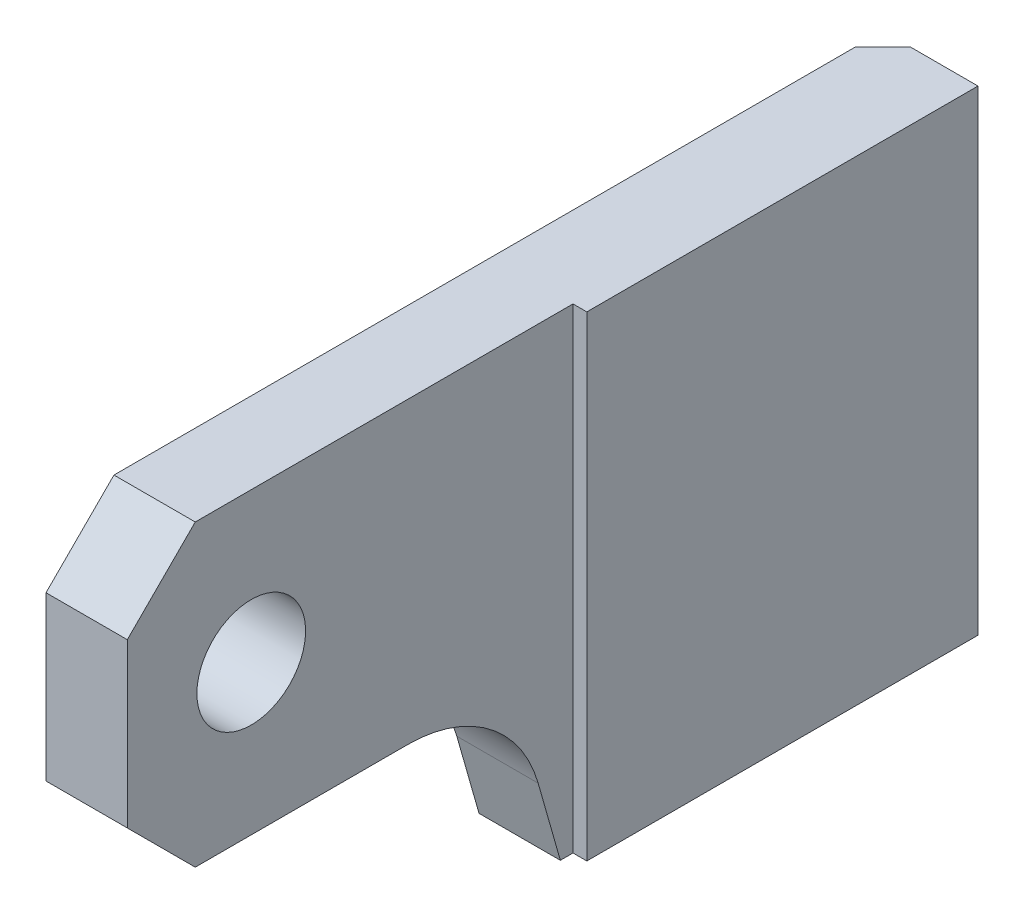
SolidWorks part; units mm, degrees
ref_plane "Спереди" through (0, 0, 0) normal (0, 0, 1) x (1, 0, 0)
ref_plane "Сверху" through (0, 0, 0) normal (0, 1, 0) x (1, 0, 0)
ref_plane "Справа" through (0, 0, 0) normal (1, 0, 0) x (0, 0, -1)
sketch "Эскиз1" plane through (0, 0, 0) normal (1, 0, 0) x (0, 0, -1)
  line L0 (62.8227, -35.8829) -> (59.12, -22.8884)
  line L1 (92.5393, -0.8884) -> (30.9567, -0.8884)
  line L2 (92.5393, -0.8884) -> (92.5393, -35.8884)
  line L3 (62.8227, -35.8829) -> (92.5393, -35.8884)
  line L4 (30.9567, -0.8884) -> (30.9567, -22.8884)
  line L5 (59.12, -22.8884) -> (30.9567, -22.8884)
extrude "Вытянуть1" add sketch "Эскиз1" against normal blind 7
fillet "Скругление1" radius 10 1 edges at (-3.5, -22.8884, -59.12)
chamfer "Фаска1" distance 5 angle 45 2 edges at (-3.5, -0.8884, -30.9567) (-3.5, -22.8884, -30.9567)
chamfer "Фаска2" distance 2 angle 45 1 edges at (-7, -18.3884, -92.5393)
sketch "Эскиз2" plane through (0, -0.8884, 0) normal (0, 1, 0) x (-1, 0, 0)
  line L1 (-21.3516, -63.7536) -> (1.0169, -63.7536)
  line L2 (-21.3516, -63.7536) -> (-21.3516, -10.597)
  line L3 (-21.3516, -10.597) -> (1.0169, -10.597)
  line L4 (1.0169, -63.7536) -> (1.0169, -10.597)
extrude "Вырез-Вытянуть1" cut sketch "Эскиз2" against normal through all
sketch "Эскиз3" plane through (-7, 0, 0) normal (-1, 0, 0) x (0, 0, 1)
  line L0 (-30.9567, -11.8884) -> (-21.3739, -11.8884) construction
  circle A0 centre (-40.0769, -11.8884) radius 4
extrude "Вырез-Вытянуть2" cut sketch "Эскиз3" against normal through all
